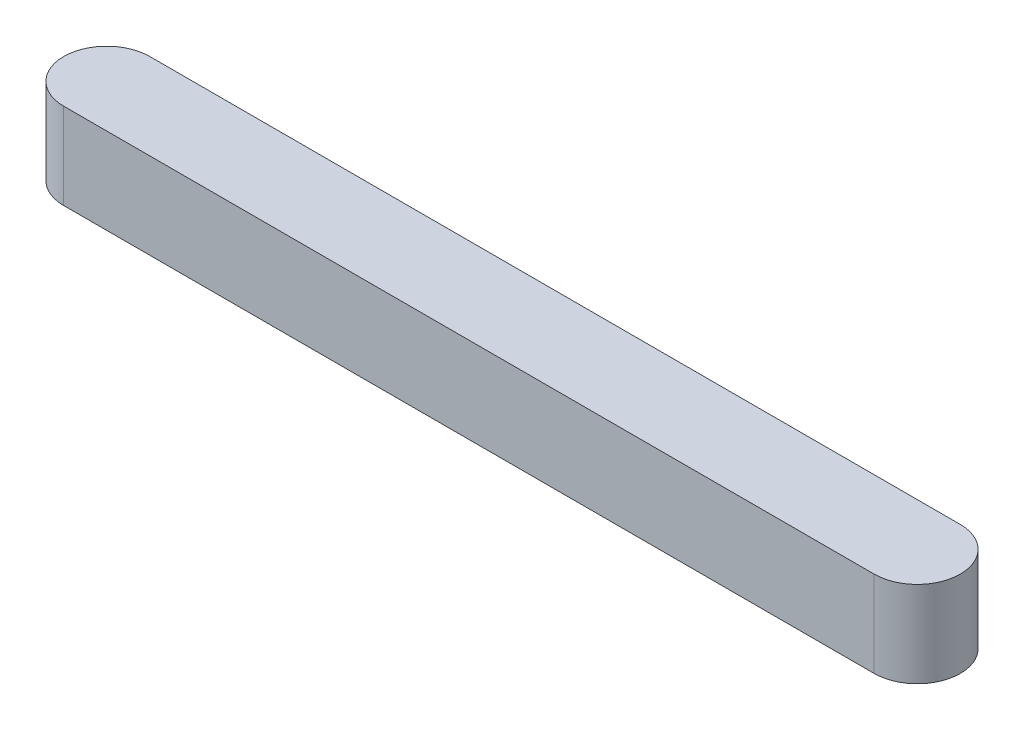
SolidWorks part; units mm, degrees
material "Cast Alloy Steel"
ref_plane "Front Plane" through (0, 0, 0) normal (0, 0, 1) x (1, 0, 0)
ref_plane "Top Plane" through (0, 0, 0) normal (0, 1, 0) x (1, 0, 0)
ref_plane "Right Plane" through (0, 0, 0) normal (1, 0, 0) x (0, 0, -1)
sketch "Sketch1" plane through (0, 0, 0) normal (0, 1, 0) x (1, 0, 0)
  line L0 (-62.5, 0) -> (62.5, 0) construction
  line L1 (-56.5, 0) -> (56.5, 0) construction
  line L2 (-56.5, 6) -> (56.5, 6)
  line L3 (-56.5, -6) -> (56.5, -6)
  arc A0 (-56.5, 6) -> (-56.5, -6) centre (-56.5, 0) ccw
  arc A1 (56.5, -6) -> (56.5, 6) centre (56.5, 0) ccw
  point P4 (0, 0)
  point P7 (0, 0)
  dimension "D" = 6
  dimension "L" = 125
extrude "Boss-Extrude1" add sketch "Sketch1" along normal blind 12
sketch "Sketch2" plane through (0, 12, 0) normal (0, 1, 0) x (1, 0, 0)
  line L0 (56.5, 6) -> (-56.5, 6) construction
  line L1 (0, 6) -> (62.5, 6)
  line L2 (0, 6) -> (0, -6)
  line L3 (0, -6) -> (62.5, -6)
  line L4 (62.5, 6) -> (62.5, -6)
  line L5 (-56.5, -6) -> (56.5, -6) construction
  arc A0 (56.5, -6) -> (56.5, 6) centre (56.5, 0) ccw construction
extrude "Cut-Extrude1" [suppressed] cut sketch "Sketch2" against normal through all
equation "\"L\"= 125"
equation "\"D\"= 6"
equation "\"H\"= 12"
equation "\"Cut-Extrude1\"= IIF ( \"L\" = 160 , \"unsuppressed\" , IIF ( \"L\" = 100 , \"unsuppressed\" , \"suppressed\" ) )"
equation "\"L@Sketch1\"=\"L\""
equation "\"D@Sketch1\"=\"D\""
equation "\"H@Boss-Extrude1\"=\"H\""
